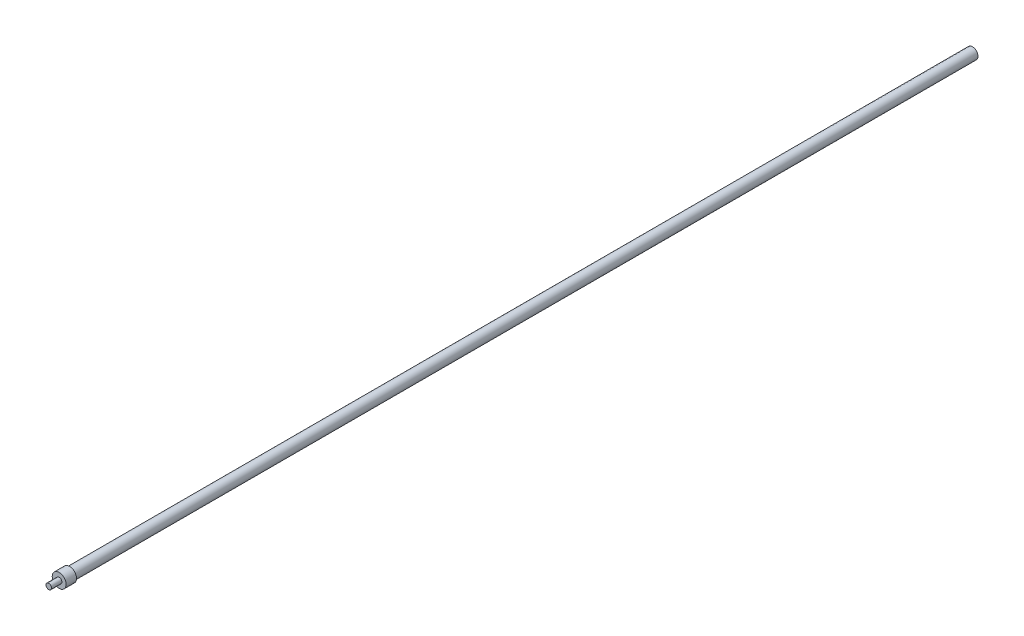
SolidWorks part; units mm, degrees
ref_plane "Alzado" through (0, 0, 0) normal (0, 0, 1) x (1, 0, 0)
ref_plane "Planta" through (0, 0, 0) normal (0, 1, 0) x (1, 0, 0)
ref_plane "Vista lateral" through (0, 0, 0) normal (1, 0, 0) x (0, 0, -1)
sketch "Croquis1" plane through (0, 0, 0) normal (0, 0, 1) x (1, 0, 0)
  circle A0 centre (0, 0) radius 6.35
  dimension "D1" = 12.7
extrude "Saliente-Extruir1" add sketch "Croquis1" along normal blind 1040
sketch "Croquis4" plane through (0, 0, 1040) normal (0, 0, 1) x (1, 0, 0)
  circle A0 centre (0, 0) radius 8
  dimension "D1" = 16
extrude "Saliente-Extruir2" add sketch "Croquis4" along normal blind 12
sketch "Croquis5" plane through (0, 0, 1052) normal (0, 0, 1) x (1, 0, 0)
  circle A0 centre (0, 0) radius 3.175
  dimension "D1" = 6.35
extrude "Saliente-Extruir3" add sketch "Croquis5" along normal blind 12
